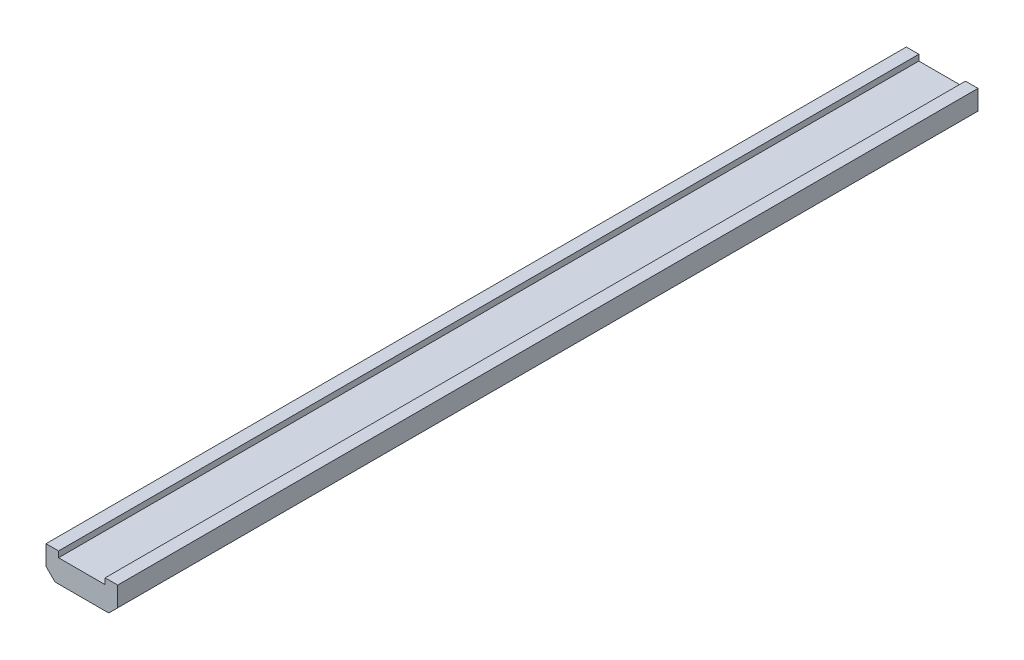
SolidWorks part; units mm, degrees
ref_plane "Front Plane" through (0, 0, 0) normal (0, 0, 1) x (1, 0, 0)
ref_plane "Top Plane" through (0, 0, 0) normal (0, 1, 0) x (1, 0, 0)
ref_plane "Right Plane" through (0, 0, 0) normal (1, 0, 0) x (0, 0, -1)
sketch "Sketch1" plane through (0, 0, 0) normal (0, 1, 0) x (1, 0, 0)
  line L1 (-100, 1200) -> (100, 1200)
  line L2 (-100, 1200) -> (-100, -1200)
  line L3 (-100, -1200) -> (100, -1200)
  line L4 (100, 1200) -> (100, -1200)
  line L5 (-100, 1200) -> (100, -1200) construction
  line L6 (-100, -1200) -> (100, 1200) construction
  point P0 (0, 0)
  point P6 (0, 0)
extrude "Boss-Extrude1" add sketch "Sketch1" along normal blind 80
chamfer "Chamfer1" distance 25 angle 45 2 edges at (-100, 0, 0) (100, 0, 0)
sketch "Sketch2" plane through (0, 80, 0) normal (0, 1, 0) x (1, 0, 0)
  line L0 (-100, -1200) -> (100, -1200) construction
  line L1 (-65, 1200) -> (65, 1200)
  line L2 (-65, 1200) -> (-65, -1200)
  line L3 (-65, -1200) -> (65, -1200)
  line L4 (65, 1200) -> (65, -1200)
  line L5 (-65, 1200) -> (65, -1200) construction
  line L6 (-65, -1200) -> (65, 1200) construction
  point P0 (0, 0)
extrude "Cut-Extrude1" cut sketch "Sketch2" against normal blind 16.5174
